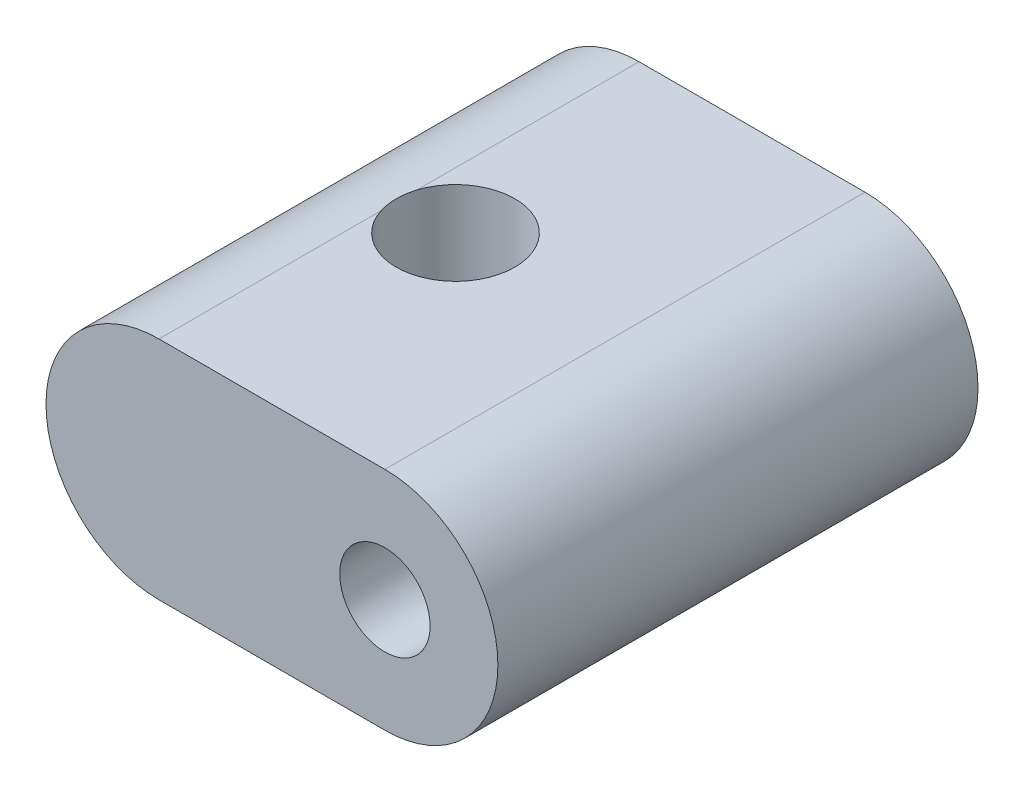
SolidWorks part; units mm, degrees
material "ABS"
ref_plane "Front Plane" through (0, 0, 0) normal (0, 0, 1) x (1, 0, 0)
ref_plane "Top Plane" through (0, 0, 0) normal (0, 1, 0) x (1, 0, 0)
ref_plane "Right Plane" through (0, 0, 0) normal (1, 0, 0) x (0, 0, -1)
sketch "Sketch1" plane through (0, 0, 5) normal (0, 0, 1) x (1, 0, 0)
  line L0 (-8, 0) -> (0, 0) construction
  line L1 (-8, -4) -> (0, -4)
  line L2 (-8, 4) -> (0, 4)
  arc A0 (0, -4) -> (0, 4) centre (0, 0) ccw
  arc A1 (-8, 4) -> (-8, -4) centre (-8, 0) ccw
  circle A2 centre (0, 0) radius 1.6
  dimension "D1" = 8
  dimension "D2" = 8
  dimension "D4" = 3.2
  dimension "D3" = 8
extrude "Boss-Extrude1" add sketch "Sketch1" along normal blind 17
sketch "Sketch2" plane through (0, 4, 0) normal (0, 1, 0) x (1, 0, 0)
  line L1 (-8, -13.5) -> (-6, -13.5) construction
  line L2 (-8, -22) -> (-8, -5) construction
  circle A0 centre (-6, -13.5) radius 2.1
  dimension "D1" = 4.2
  dimension "1" = 2
extrude "Cut-Extrude1" cut sketch "Sketch2" against normal through all
